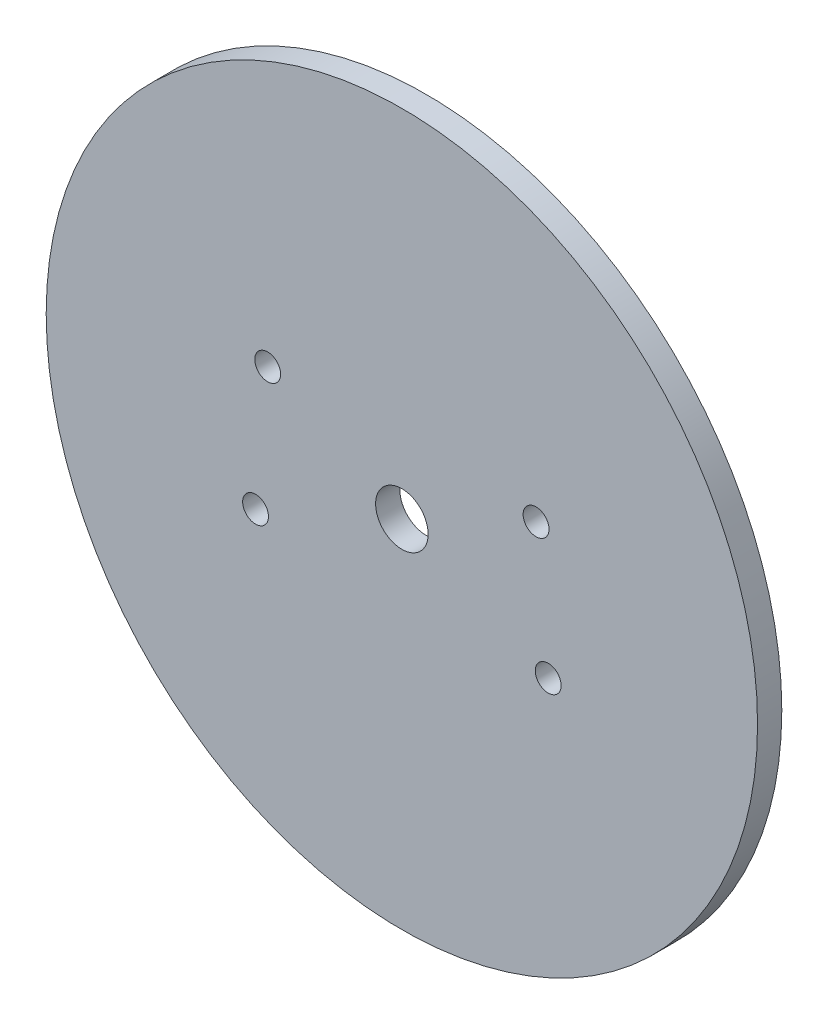
SolidWorks part; units mm, degrees
ref_plane "正面" through (0, 0, 0) normal (0, 0, 1) x (1, 0, 0)
ref_plane "平面" through (0, 0, 0) normal (0, 1, 0) x (1, 0, 0)
ref_plane "右側面" through (0, 0, 0) normal (1, 0, 0) x (0, 0, -1)
sketch "ｽｹｯﾁ1" plane through (0, 0, 0) normal (0, 0, 1) x (1, 0, 0)
  circle A0 centre (0, 0) radius 44
  dimension "D1" = 88
extrude "ﾎﾞｽ - 押し出し1" add sketch "ｽｹｯﾁ1" along normal blind 3
sketch "ｽｹｯﾁ2" plane through (0, 0, 3) normal (0, 0, 1) x (1, 0, 0)
  line L0 (0, 0) -> (-16.6, 0)
  line L1 (-16.6, 0) -> (-16.6, 8)
  line L2 (-16.6, 0) -> (-18.1, 0)
  line L3 (-18.1, 0) -> (-18.1, -8)
  line L4 (0, 0) -> (0, 15.9532)
  circle A0 centre (-16.6, 8) radius 1.6
  circle A1 centre (-18.1, -8) radius 1.6
  circle A2 centre (18.1, -8) radius 1.6
  circle A3 centre (16.6, 8) radius 1.6
  dimension "D5" = 3.2
  dimension "D6" = 3.2
  dimension "D1" = 16.6
  dimension "D2" = 8
  dimension "D3" = 1.5
  dimension "D4" = 8
extrude "ｶｯﾄ - 押し出し1" cut sketch "ｽｹｯﾁ2" against normal blind 3 contours A1 | A0 | A2 | A3
sketch "ｽｹｯﾁ3" plane through (0, 0, 3) normal (0, 0, 1) x (1, 0, 0)
  circle A0 centre (0, 0) radius 3.25
  dimension "D1" = 6.5
extrude "ｶｯﾄ - 押し出し2" cut sketch "ｽｹｯﾁ3" against normal blind 35
